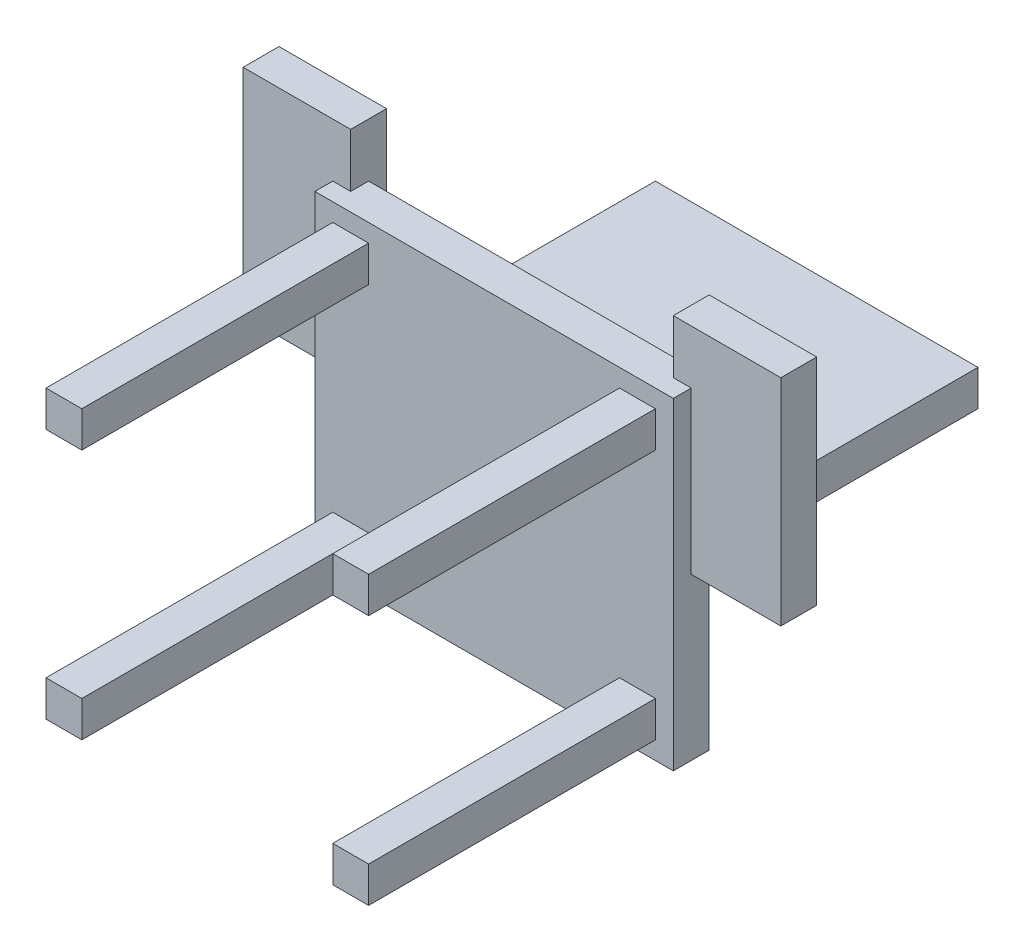
SolidWorks part; units mm, degrees
ref_plane "前视基准面" through (0, 0, 0) normal (0, 0, 1) x (1, 0, 0)
ref_plane "上视基准面" through (0, 0, 0) normal (0, 1, 0) x (1, 0, 0)
ref_plane "右视基准面" through (0, 0, 0) normal (1, 0, 0) x (0, 0, -1)
other "Configuration Table"
sketch "草图1" plane through (0, 0, 0) normal (0, 0, 1) x (1, 0, 0)
  line L1 (-250, -225) -> (250, -225)
  line L2 (-250, -225) -> (-250, 225)
  line L3 (-250, 225) -> (250, 225)
  line L4 (250, -225) -> (250, 225)
  line L5 (-250, -225) -> (250, 225) construction
  line L6 (-250, 225) -> (250, -225) construction
  point P0 (0, 0)
extrude "凸台-拉伸1" add sketch "草图1" along normal blind 50
sketch "草图2" plane through (0, 0, 0) normal (0, 0, 1) x (1, 0, 0)
  line L1 (-225, -200) -> (-175, -200)
  line L2 (-225, -200) -> (-225, -150)
  line L3 (-225, -150) -> (-175, -150)
  line L4 (-175, -200) -> (-175, -150)
  line L5 (-225, -200) -> (-175, -150) construction
  line L6 (-225, -150) -> (-175, -200) construction
  point P0 (-200, -175)
extrude "凸台-拉伸2" add sketch "草图2" along normal blind 450
sketch "草图3" plane through (0, 0, 0) normal (0, 0, 1) x (1, 0, 0)
  line L1 (175, -200) -> (225, -200)
  line L2 (175, -200) -> (175, -150)
  line L3 (175, -150) -> (225, -150)
  line L4 (225, -200) -> (225, -150)
  line L5 (175, -200) -> (225, -150) construction
  line L6 (175, -150) -> (225, -200) construction
  point P0 (200, -175)
extrude "凸台-拉伸3" add sketch "草图3" along normal blind 450
sketch "草图4" plane through (0, 0, 0) normal (0, 0, 1) x (1, 0, 0)
  line L1 (-225, 150) -> (-175, 150)
  line L2 (-225, 150) -> (-225, 200)
  line L3 (-225, 200) -> (-175, 200)
  line L4 (-175, 150) -> (-175, 200)
  line L5 (-225, 150) -> (-175, 200) construction
  line L6 (-225, 200) -> (-175, 150) construction
  point P0 (-200, 175)
extrude "凸台-拉伸4" add sketch "草图4" along normal blind 450
sketch "草图5" plane through (0, 0, 0) normal (0, 0, 1) x (1, 0, 0)
  line L1 (175, 150) -> (225, 150)
  line L2 (175, 150) -> (175, 200)
  line L3 (175, 200) -> (225, 200)
  line L4 (225, 150) -> (225, 200)
  line L5 (175, 150) -> (225, 200) construction
  line L6 (175, 200) -> (225, 150) construction
  point P0 (200, 175)
extrude "凸台-拉伸5" add sketch "草图5" along normal blind 450
sketch "草图6" plane through (0, 0, 0) normal (0, 0, -1) x (-1, 0, 0)
  line L1 (-225, -25) -> (225, -25)
  line L2 (-225, -25) -> (-225, 25)
  line L3 (-225, 25) -> (225, 25)
  line L4 (225, -25) -> (225, 25)
  line L5 (-225, -25) -> (225, 25) construction
  line L6 (-225, 25) -> (225, -25) construction
  point P0 (0, 0)
extrude "凸台-拉伸6" add sketch "草图6" along normal blind 400
sketch "草图7" plane through (-225, 0, 0) normal (-1, 0, 0) x (0, 0, 1)
  line L0 (0, 225) -> (0, -225) construction
  line L1 (-25, 0) -> (25, 0)
  line L2 (-25, 0) -> (-25, 300)
  line L3 (-25, 300) -> (25, 300)
  line L4 (25, 0) -> (25, 300)
  line L5 (-25, 0) -> (25, 300) construction
  line L6 (-25, 300) -> (25, 0) construction
  point P0 (0, 150)
extrude "凸台-拉伸7" add sketch "草图7" along normal blind 150
sketch "草图8" plane through (225, 0, 0) normal (1, 0, 0) x (0, 0, -1)
  line L0 (0, -225) -> (0, 225) construction
  line L1 (-25, 0) -> (25, 0)
  line L2 (-25, 0) -> (-25, 300)
  line L3 (-25, 300) -> (25, 300)
  line L4 (25, 0) -> (25, 300)
  line L5 (-25, 0) -> (25, 300) construction
  line L6 (-25, 300) -> (25, 0) construction
  point P0 (0, 150)
extrude "凸台-拉伸8" add sketch "草图8" along normal blind 150
